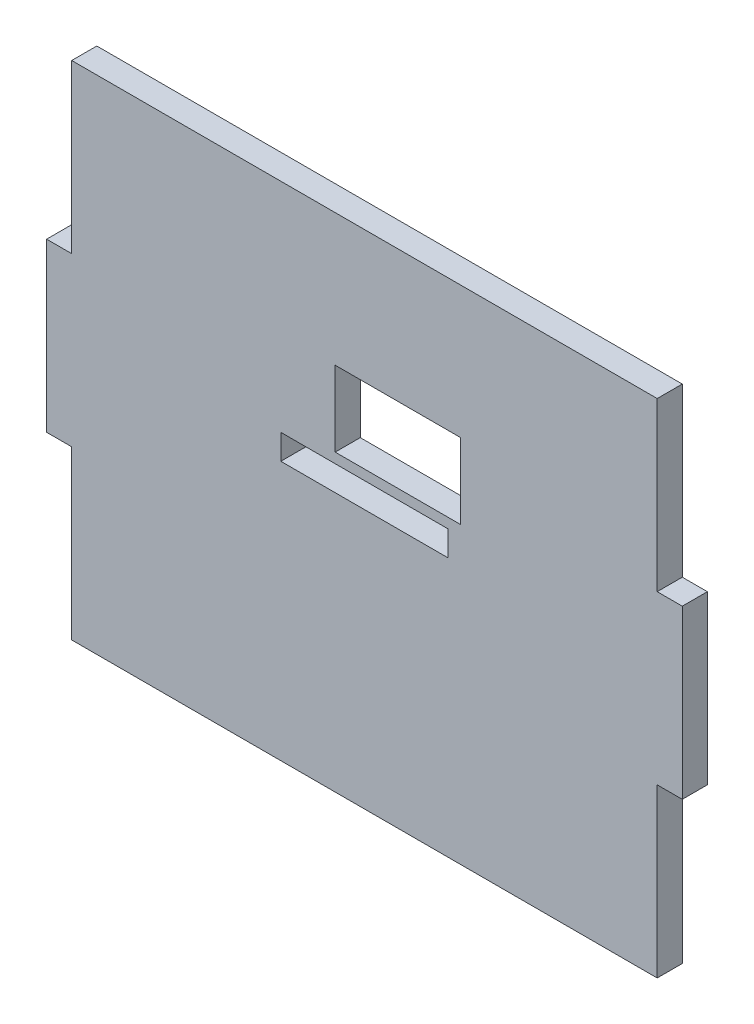
SolidWorks part; units mm, degrees
ref_plane "Front Plane" through (0, 0, 0) normal (0, 0, 1) x (1, 0, 0)
ref_plane "Top Plane" through (0, 0, 0) normal (0, 1, 0) x (1, 0, 0)
ref_plane "Right Plane" through (0, 0, 0) normal (1, 0, 0) x (0, 0, -1)
sketch "Sketch1" plane through (0, 0, 0) normal (0, 0, 1) x (1, 0, 0)
  line L1 (-35, 30) -> (35, 30)
  line L2 (-35, 30) -> (-35, -30)
  line L3 (-35, -30) -> (35, -30)
  line L4 (35, 30) -> (35, -30)
  line L5 (-35, 30) -> (35, -30) construction
  line L6 (-35, -30) -> (35, 30) construction
  point P0 (0, 0)
  dimension "D1" = 70
  dimension "D2" = 60
extrude "Boss-Extrude1" add sketch "Sketch1" along normal blind 3
sketch "Sketch2" plane through (0, 0, 3) normal (0, 0, 1) x (1, 0, 0)
  line L0 (-35, -30) -> (35, -30) construction
  line L1 (-3.5, 14.2) -> (11.5, 14.2)
  line L2 (-3.5, 14.2) -> (-3.5, 5.2)
  line L3 (-3.5, 5.2) -> (11.5, 5.2)
  line L4 (11.5, 14.2) -> (11.5, 5.2)
  line L5 (-3.5, 14.2) -> (11.5, 5.2) construction
  line L6 (-3.5, 5.2) -> (11.5, 14.2) construction
  line L7 (35, -30) -> (35, 30) construction
  point P0 (4, 9.7)
  dimension "D1" = 9
  dimension "D2" = 15
  dimension "D3" = 39.7
  dimension "D4" = 31
extrude "Cut-Extrude1" cut sketch "Sketch2" against normal blind 3
sketch "Sketch3" plane through (0, 0, 3) normal (0, 0, 1) x (1, 0, 0)
  line L0 (-35, -30) -> (35, -30) construction
  line L1 (10, 4) -> (-10, 4)
  line L2 (10, 4) -> (10, 1)
  line L3 (10, 1) -> (-10, 1)
  line L4 (-10, 4) -> (-10, 1)
  line L5 (10, 4) -> (-10, 1) construction
  line L6 (10, 1) -> (-10, 4) construction
  line L7 (0, 2.5) -> (0, -30) construction
  point P0 (0, 2.5)
  dimension "D1" = 3
  dimension "D2" = 20
  dimension "D3" = 31
extrude "Cut-Extrude2" cut sketch "Sketch3" against normal blind 3
sketch "Sketch4" plane through (0, 0, 3) normal (0, 0, 1) x (1, 0, 0)
  line L0 (0, 0) -> (36.5, 0) construction
  line L1 (38, 10) -> (35, 10)
  line L2 (38, 10) -> (38, -10)
  line L3 (38, -10) -> (35, -10)
  line L4 (35, 10) -> (35, -10)
  line L5 (38, 10) -> (35, -10) construction
  line L6 (38, -10) -> (35, 10) construction
  line L7 (-35, 10) -> (-38, 10)
  line L8 (-35, 10) -> (-35, -10)
  line L9 (-35, -10) -> (-38, -10)
  line L10 (-38, 10) -> (-38, -10)
  line L11 (-35, 10) -> (-38, -10) construction
  line L12 (-35, -10) -> (-38, 10) construction
  line L13 (0, 0) -> (-36.5, 0) construction
  line L14 (-35, 30) -> (-35, -30) construction
  line L15 (35, -30) -> (35, 30) construction
  point P0 (36.5, 0)
  point P5 (-36.5, 0)
  dimension "D1" = 20
  dimension "D2" = 3
extrude "Boss-Extrude2" add sketch "Sketch4" against normal up to surface (3 mm away) up to face at (0, 2.5, 0)
